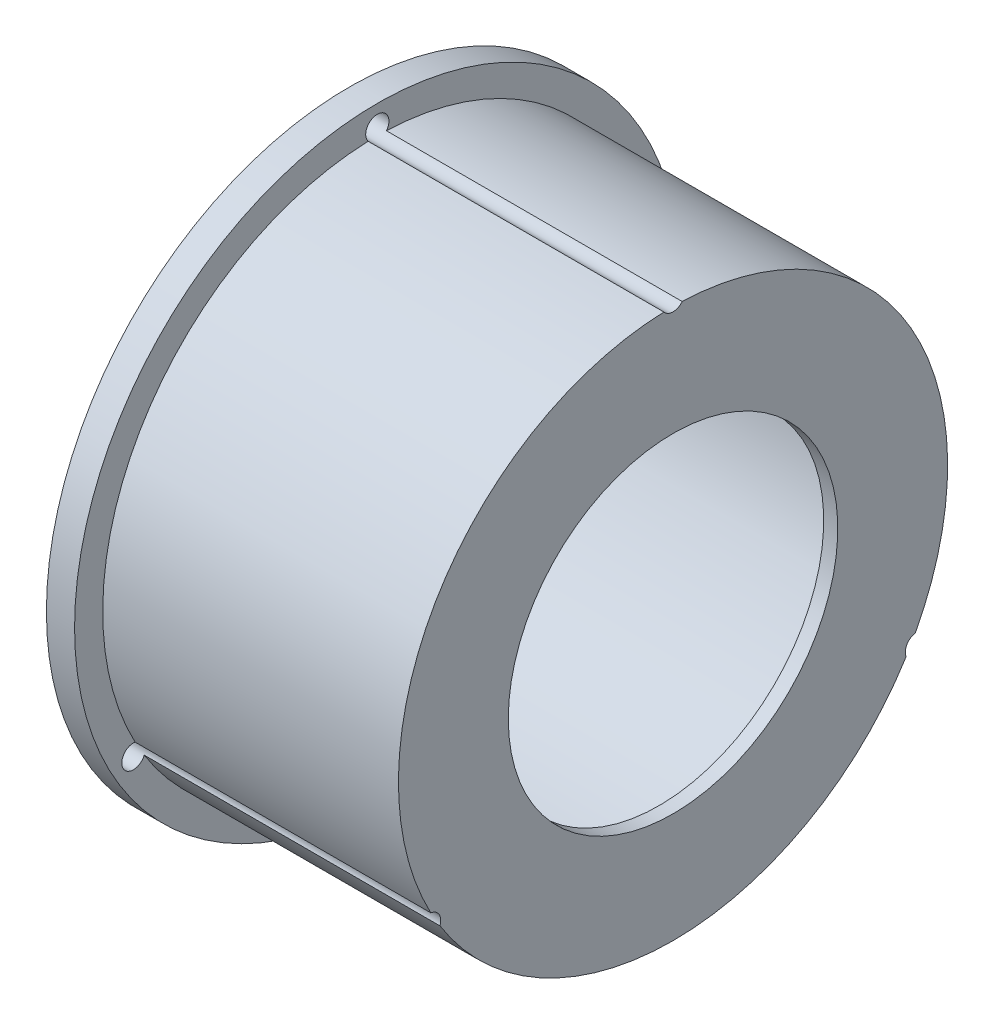
SolidWorks part; units mm, degrees
ref_plane "Front Plane" through (0, 0, 0) normal (0, 0, 1) x (1, 0, 0)
ref_plane "Top Plane" through (0, 0, 0) normal (0, 1, 0) x (1, 0, 0)
ref_plane "Right Plane" through (0, 0, 0) normal (1, 0, 0) x (0, 0, -1)
sketch "Axial profile (mm)" plane through (0, 0, 0) normal (0, 0, 1) x (1, 0, 0)
  line L0 (-110, 0) -> (75, 0) construction
  line L1 (135.7, 36.4) -> (179.7, 36.4)
  line L2 (179.7, 36.4) -> (179.7, 23.4)
  line L3 (179.7, 23.4) -> (181.7, 23.4)
  line L4 (181.7, 23.4) -> (181.7, 39)
  line L5 (181.7, 39) -> (139.7, 39)
  line L6 (139.7, 39) -> (139.7, 43)
  line L7 (139.7, 43) -> (135.7, 43)
  line L8 (135.7, 43) -> (135.7, 36.4)
revolve "Full revolution" add sketch "Axial profile (mm)" angle 360 about L0
sketch "Sketch2" plane through (0, 0, 0) normal (1, 0, 0) x (0, 0, -1)
  circle A0 centre (0, 40) radius 1.65
  circle A1 centre (-34.641, -20) radius 1.65
  circle A2 centre (34.641, -20) radius 1.65
extrude "Axial holes" cut sketch "Sketch2" against normal through all and the other way through all
